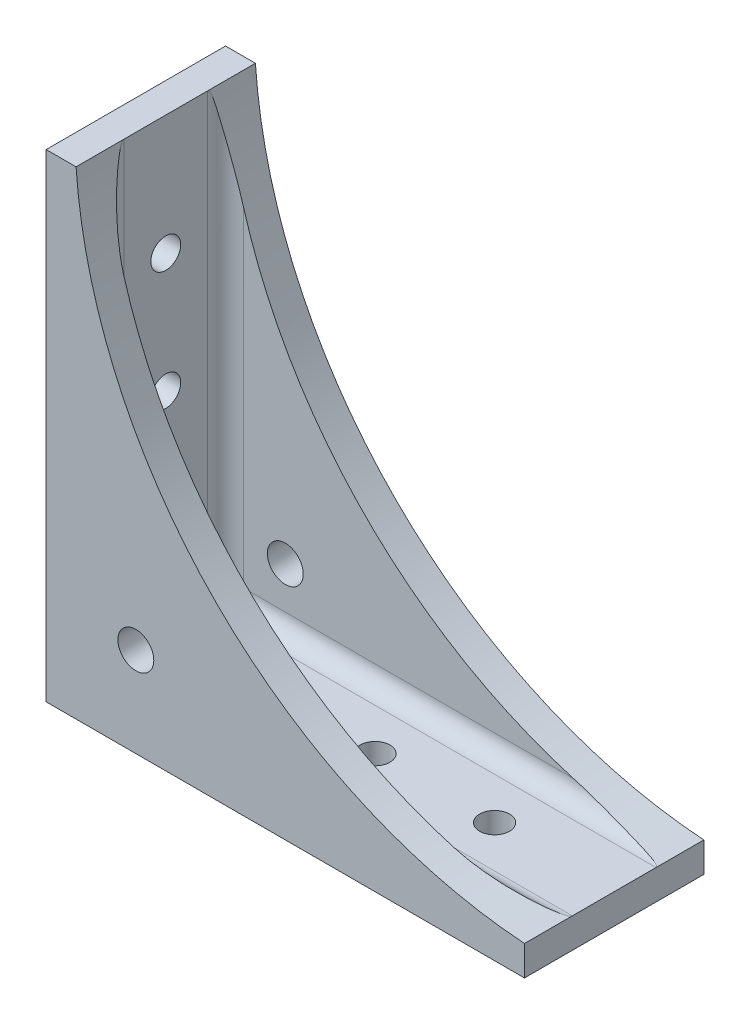
SolidWorks part; units mm, degrees
ref_plane "Front Plane" through (0, 0, 0) normal (0, 0, 1) x (1, 0, 0)
ref_plane "Top Plane" through (0, 0, 0) normal (0, 1, 0) x (1, 0, 0)
ref_plane "Right Plane" through (0, 0, 0) normal (1, 0, 0) x (0, 0, -1)
sketch "Sketch4" plane through (0, 0, 0) normal (0, 0, 1) x (1, 0, 0)
  line L0 (0, 0) -> (0, 80)
  line L1 (0, 80) -> (5, 80)
  line L2 (5, 80) -> (5, 5)
  line L3 (5, 5) -> (80, 5)
  line L4 (80, 5) -> (80, 0)
  line L5 (80, 0) -> (0, 0)
extrude "Boss-Extrude2" add sketch "Sketch4" along normal blind 30
sketch "Sketch5" plane through (0, 5, 0) normal (0, 1, 0) x (1, 0, 0)
  circle A0 centre (60, -15) radius 2.5
  circle A1 centre (40, -15) radius 2.5
extrude "Cut-Extrude3" cut sketch "Sketch5" against normal blind 6
sketch "Sketch6" plane through (5, 0, 0) normal (1, 0, 0) x (0, 0, -1)
  circle A0 centre (-15, 60) radius 2.5
  circle A1 centre (-15, 40) radius 2.5
extrude "Cut-Extrude4" cut sketch "Sketch6" against normal blind 6
sketch "Sketch7" plane through (0, 0, 0) normal (0, 0, -1) x (-1, 0, 0)
  line L0 (-5, 80) -> (-5, 5)
  line L1 (-5, 5) -> (-80, 5)
  line L2 (-80, 5) -> (-5, 80)
extrude "Boss-Extrude3" add sketch "Sketch7" against normal blind 5
sketch "Sketch8" plane through (0, 0, 30) normal (0, 0, 1) x (1, 0, 0)
  line L0 (5, 80) -> (5, 5)
  line L1 (5, 5) -> (80, 5)
  line L2 (80, 5) -> (5, 80)
extrude "Boss-Extrude4" add sketch "Sketch8" against normal blind 5
fillet "Fillet1" radius 3 1 edges at (5, 42.5, 25)
fillet "Fillet2" radius 3 1 edges at (5, 42.5, 5)
fillet "Fillet3" radius 3 5 edges at (44, 5, 5) (5.8787, 5, 5.8787) (5, 5, 15) (5.8787, 5, 24.1213) (44, 5, 25)
sketch "Sketch9" plane through (0, 0, 30) normal (0, 0, 1) x (1, 0, 0)
  line L0 (5, 80) -> (80, 5)
  arc A0 (80, 5) -> (5, 80) centre (85.7217, 85.7217) cw
extrude "Cut-Extrude5" cut sketch "Sketch9" against normal through all
sketch "Sketch10" plane through (0, 0, 30) normal (0, 0, 1) x (1, 0, 0)
  line L0 (0, 80) -> (0, 0) construction
  line L1 (0, 0) -> (80, 0) construction
  circle A0 centre (15, 15) radius 3
  dimension "D1" = 15
  dimension "D2" = 15
extrude "Cut-Extrude6" cut sketch "Sketch10" against normal through all
